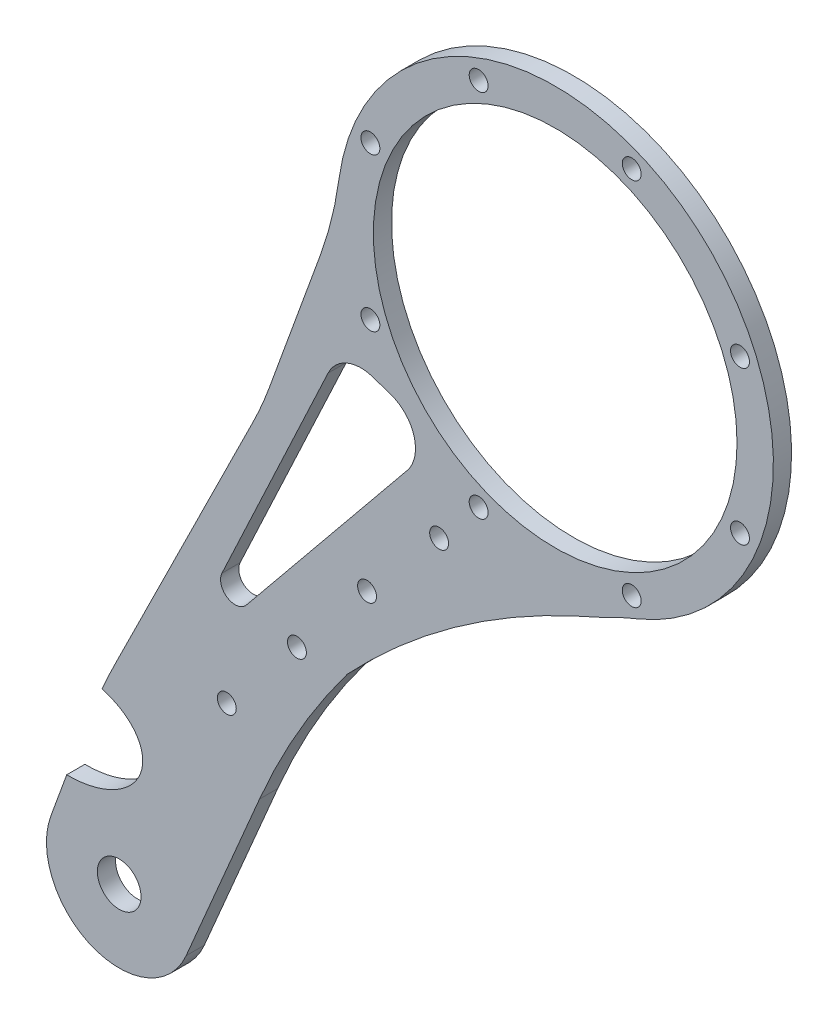
SolidWorks part; units mm, degrees
ref_plane "前视基准面" through (0, 0, 0) normal (0, 0, 1) x (1, 0, 0)
ref_plane "上视基准面" through (0, 0, 0) normal (0, 1, 0) x (1, 0, 0)
ref_plane "右视基准面" through (0, 0, 0) normal (1, 0, 0) x (0, 0, -1)
other "Configuration Table"
sketch "草图1" plane through (0, 0, 0) normal (0, 0, 1) x (1, 0, 0)
  line L0 (-5.5363, 38.4154) -> (-10.5146, 40.1229)
  line L1 (-45.2748, -31.5571) -> (-1.0344, 22.6322)
  line L2 (-22.8132, 34.9091) -> (-51.995, -27.3294)
  line L3 (45.3404, 11.1139) -> (52.9869, 14.6126)
  line L4 (-24.9203, 61.9741) -> (-38.9923, 23.3116)
  line L5 (-43.3475, 13.1367) -> (-81.2946, -63.4932)
  line L6 (-94.6733, -96.6691) -> (-99.0395, -108.6652)
  line L7 (-61.8447, -123.3417) -> (-41.6659, -75.9577)
  circle A0 centre (84.1333, 74.485) radius 1.85
  circle A1 centre (-4.8667, 74.485) radius 1.85
  circle A2 centre (71.0995, 43.0187) radius 1.85
  circle A3 centre (-80.2456, -115.5056) radius 6
  circle A4 centre (71.0995, 105.9512) radius 1.85
  circle A5 centre (39.6333, 29.985) radius 1.85
  circle A6 centre (8.167, 43.0187) radius 1.85
  circle A7 centre (8.167, 105.9512) radius 1.85
  circle A8 centre (39.6333, 118.985) radius 1.85
  circle A9 centre (90.4466, 95.5326) radius 2.6
  circle A10 centre (60.6808, 125.2984) radius 2.6
  circle A11 centre (18.5857, 125.2984) radius 2.6
  circle A12 centre (-11.1801, 95.5326) radius 2.6
  circle A13 centre (-11.1801, 53.4374) radius 2.6
  circle A14 centre (18.5857, 23.6716) radius 2.6
  circle A15 centre (60.6808, 23.6716) radius 2.6
  circle A16 centre (90.4466, 53.4374) radius 2.6
  circle A17 centre (-31.3758, -34.648) radius 2.6
  circle A18 centre (7.7182, 10.8622) radius 2.6
  circle A19 centre (-12.0922, -11.6667) radius 2.6
  circle A20 centre (-50.6595, -57.6293) radius 2.6
  circle A21 centre (39.6333, 74.485) radius 40
  arc A22 (-10.5146, 40.1229) -> (-22.8132, 34.9091) centre (-13.759, 30.6639) ccw
  arc A23 (-1.0344, 22.6322) -> (-5.5363, 38.4154) centre (-8.7808, 28.9563) ccw
  arc A24 (-51.995, -27.3294) -> (-45.2748, -31.5571) centre (-48.3733, -29.0275) ccw
  arc A25 (-17.5395, -34.1635) -> (-41.6659, -75.9577) centre (142.3435, -154.3194) ccw
  arc A26 (45.3404, 11.1139) -> (-17.5395, -34.1635) centre (128.5543, -170.7527) ccw
  arc A27 (62.1409, 18.8666) -> (52.9869, 14.6126) centre (99.6535, -73.8308) ccw
  arc A28 (62.1409, 18.8666) -> (-19.8128, 82.6192) centre (39.6333, 74.485) ccw
  arc A29 (-24.9203, 61.9741) -> (-19.8128, 82.6192) centre (-118.8896, 96.1761) ccw
  arc A30 (-43.3475, 13.1367) -> (-38.9923, 23.3116) centre (-132.9616, 57.5136) ccw
  arc A31 (-81.2946, -63.4932) -> (-84.9679, -71.3332) centre (97.9336, -152.247) ccw
  arc A32 (-99.0395, -108.6652) -> (-61.8447, -123.3417) centre (-80.2456, -115.5056) ccw
  ellipse E0 centre (-93.3851, -83.4826) end of major axis (-112.9824, -84.5339) minor radius 13.1666 (-94.6733, -96.6691) -> (-84.9679, -71.3332) ccw
extrude "凸台-拉伸1" add sketch "草图1" along normal blind 5
sketch "草图2" plane through (0, 0, 5) normal (0, 0, 1) x (1, 0, 0)
  line L5 (45.3404, 11.1139) -> (52.9869, 14.6126)
  line L6 (-24.9203, 61.9741) -> (-38.9923, 23.3116)
  line L7 (-43.3475, 13.1367) -> (-81.2946, -63.4932)
  line L8 (-94.6733, -96.6691) -> (-99.0395, -108.6652)
  line L9 (-61.8447, -123.3417) -> (-41.6659, -75.9577)
  line L10 (45.3404, 11.1139) -> (52.9869, 14.6126)
  line L11 (-24.9203, 61.9741) -> (-38.9923, 23.3116)
  line L12 (-43.3475, 13.1367) -> (-81.2946, -63.4932)
  line L13 (-94.6733, -96.6691) -> (-99.0395, -108.6652)
  line L14 (-61.8447, -123.3417) -> (-41.6659, -75.9577)
  circle A0 centre (39.6333, 74.485) radius 50
  arc A8 (45.3404, 11.1139) -> (-17.5395, -34.1635) centre (128.5543, -170.7527) ccw
  arc A9 (62.1409, 18.8666) -> (52.9869, 14.6126) centre (99.6535, -73.8308) ccw
  arc A10 (62.1409, 18.8666) -> (-19.8128, 82.6192) centre (39.6333, 74.485) ccw
  arc A11 (-24.9203, 61.9741) -> (-19.8128, 82.6192) centre (-118.8896, 96.1761) ccw
  arc A12 (-43.3475, 13.1367) -> (-38.9923, 23.3116) centre (-132.9616, 57.5136) ccw
  arc A13 (-81.2946, -63.4932) -> (-84.9679, -71.3332) centre (97.9336, -152.247) ccw
  arc A14 (-99.0395, -108.6652) -> (-61.8447, -123.3417) centre (-80.2456, -115.5056) ccw
  arc A15 (-17.5395, -34.1635) -> (-41.6659, -75.9577) centre (142.3435, -154.3194) ccw
  arc A16 (45.3404, 11.1139) -> (-17.5395, -34.1635) centre (128.5543, -170.7527) ccw
  arc A17 (62.1409, 18.8666) -> (52.9869, 14.6126) centre (99.6535, -73.8308) ccw
  arc A18 (62.1409, 18.8666) -> (-19.8128, 82.6192) centre (39.6333, 74.485) ccw
  arc A19 (-24.9203, 61.9741) -> (-19.8128, 82.6192) centre (-118.8896, 96.1761) ccw
  arc A20 (-43.3475, 13.1367) -> (-38.9923, 23.3116) centre (-132.9616, 57.5136) ccw
  arc A21 (-81.2946, -63.4932) -> (-84.9679, -71.3332) centre (97.9336, -152.247) ccw
  arc A22 (-99.0395, -108.6652) -> (-61.8447, -123.3417) centre (-80.2456, -115.5056) ccw
  arc A23 (-17.5395, -34.1635) -> (-41.6659, -75.9577) centre (142.3435, -154.3194) ccw
  ellipse E1 centre (-93.3851, -83.4826) end of major axis (-73.7878, -82.4313) minor radius 13.1666 (-94.6733, -96.6691) -> (-84.9679, -71.3332) ccw
  ellipse E2 centre (-93.3851, -83.4826) end of major axis (-73.7878, -82.4313) minor radius 13.1666 (-94.6733, -96.6691) -> (-84.9679, -71.3332) ccw
  dimension "D2" = 100
  dimension "D1" = 0
extrude "切除-拉伸1" cut sketch "草图2" against normal blind 5 contours A0
